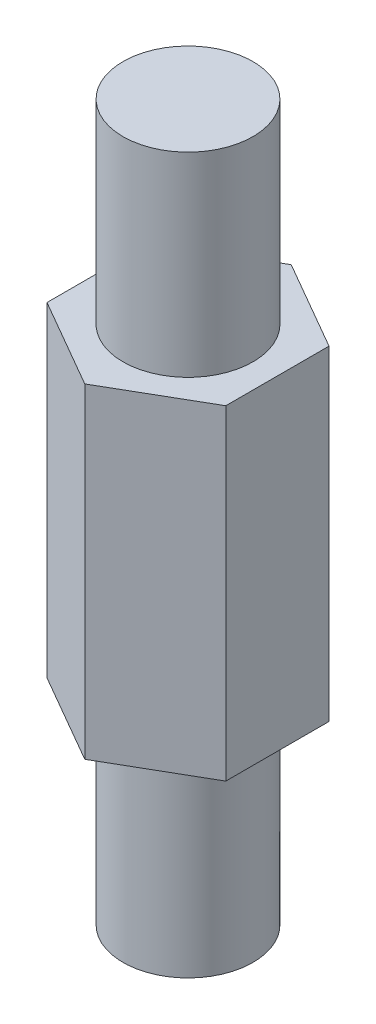
SolidWorks part; units mm, degrees
ref_plane "Спереди" through (0, 0, 0) normal (0, 0, 1) x (1, 0, 0)
ref_plane "Сверху" through (0, 0, 0) normal (0, 1, 0) x (1, 0, 0)
ref_plane "Справа" through (0, 0, 0) normal (1, 0, 0) x (0, 0, -1)
sketch "Эскиз1" plane through (0, 0, 0) normal (0, 1, 0) x (1, 0, 0)
  line L1 (0, -3.1754) -> (2.75, -1.5877)
  line L2 (2.75, -1.5877) -> (2.75, 1.5877)
  line L3 (2.75, 1.5877) -> (0, 3.1754)
  line L4 (0, 3.1754) -> (-2.75, 1.5877)
  line L5 (-2.75, 1.5877) -> (-2.75, -1.5877)
  line L6 (-2.75, -1.5877) -> (0, -3.1754)
  circle A0 centre (0, 0) radius 2.75 construction
  point P1 (0, -3.1754)
  dimension "D1" = 5.5
extrude "Бобышка-Вытянуть1" add sketch "Эскиз1" along normal blind 10
sketch "Эскиз2" plane through (0, 10, 0) normal (0, 1, 0) x (1, 0, 0)
  circle A0 centre (0, 0) radius 2
  dimension "D1" = 4
extrude "Бобышка-Вытянуть4" add sketch "Эскиз2" along normal blind 6 separate body
sketch "Эскиз3" plane through (0, 0, 0) normal (0, -1, 0) x (1, 0, 0)
  circle A0 centre (0, 0) radius 2
  circle A1 centre (0, 0) radius 2 construction
extrude "Бобышка-Вытянуть5" add sketch "Эскиз3" along normal blind 6
